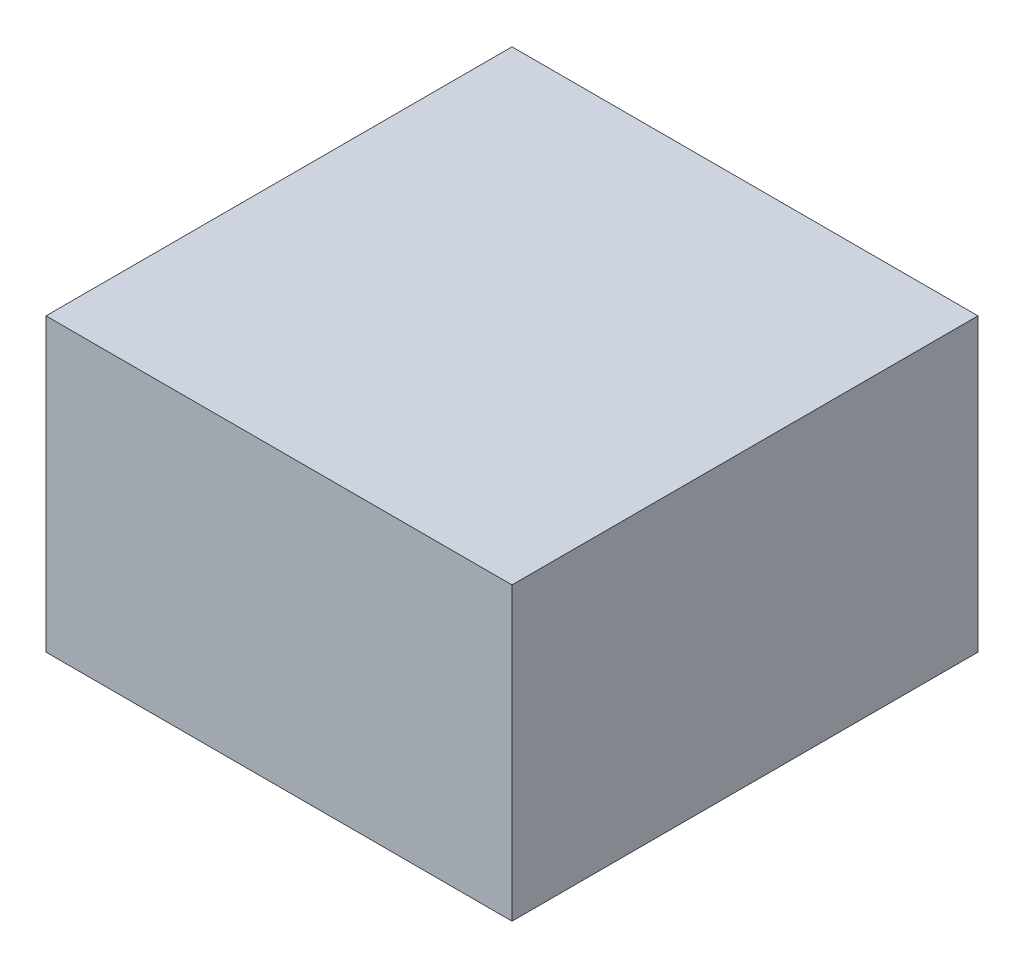
SolidWorks part; units mm, degrees
ref_plane "前视基准面" through (0, 0, 0) normal (0, 0, 1) x (1, 0, 0)
ref_plane "上视基准面" through (0, 0, 0) normal (0, 1, 0) x (1, 0, 0)
ref_plane "右视基准面" through (0, 0, 0) normal (1, 0, 0) x (0, 0, -1)
other "Configuration Table"
sketch "草图1" plane through (0, 0, 0) normal (0, 0, 1) x (1, 0, 0)
  line L0 (0, 0) -> (40, 0)
  line L1 (40, 0) -> (40, 25)
  line L2 (40, 25) -> (0, 25)
  line L3 (0, 25) -> (0, 0)
  dimension "width" = 40
  dimension "height" = 25
extrude "Camera_Module" add sketch "草图1" along normal blind 40
